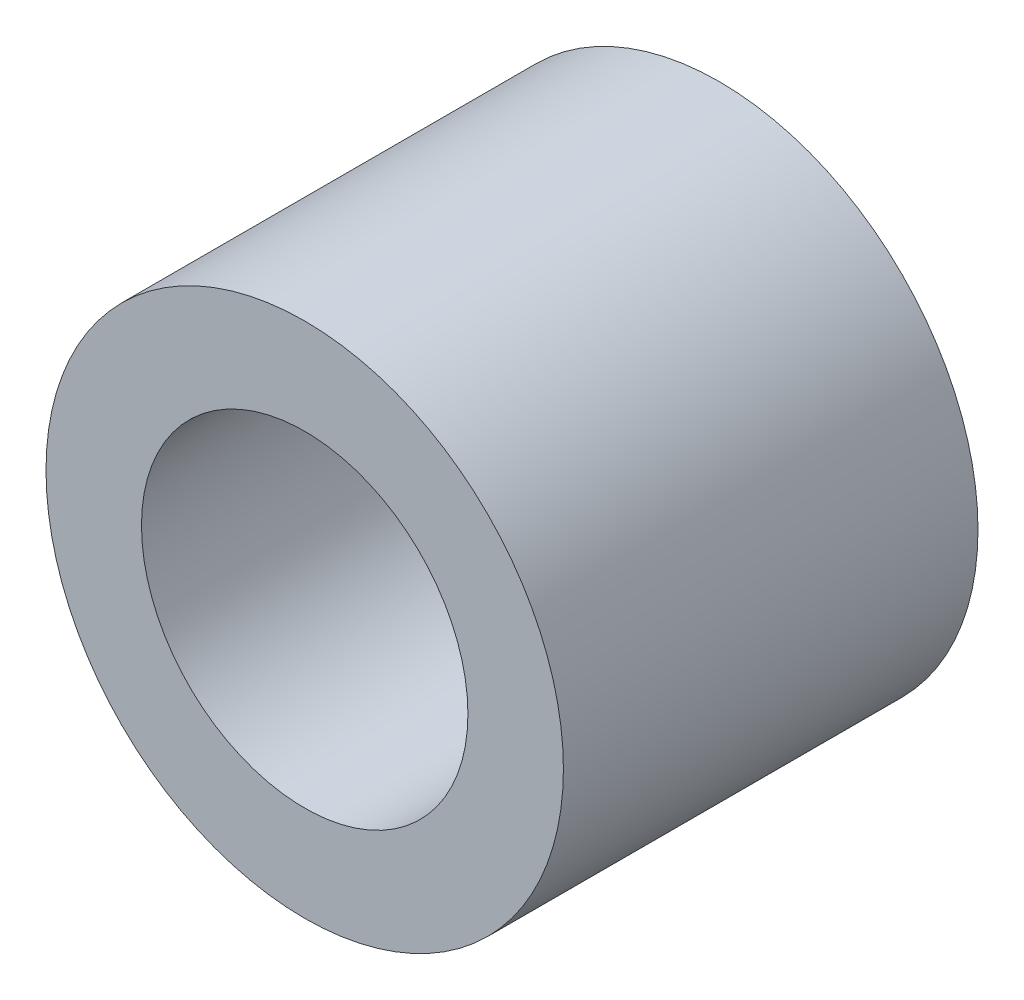
SolidWorks part; units mm, degrees
ref_plane "Front Plane" through (0, 0, 0) normal (0, 0, 1) x (1, 0, 0)
ref_plane "Top Plane" through (0, 0, 0) normal (0, 1, 0) x (1, 0, 0)
ref_plane "Right Plane" through (0, 0, 0) normal (1, 0, 0) x (0, 0, -1)
sketch "Sketch1" plane through (0, 0, 0) normal (0, 0, 1) x (1, 0, 0)
  circle A0 centre (0, 0) radius 2.5
  circle A1 centre (0, 0) radius 3.9624
  dimension "D1" = 5
  dimension "D2" = 7.9248
extrude "Boss-Extrude1" add sketch "Sketch1" along normal blind 6.35
